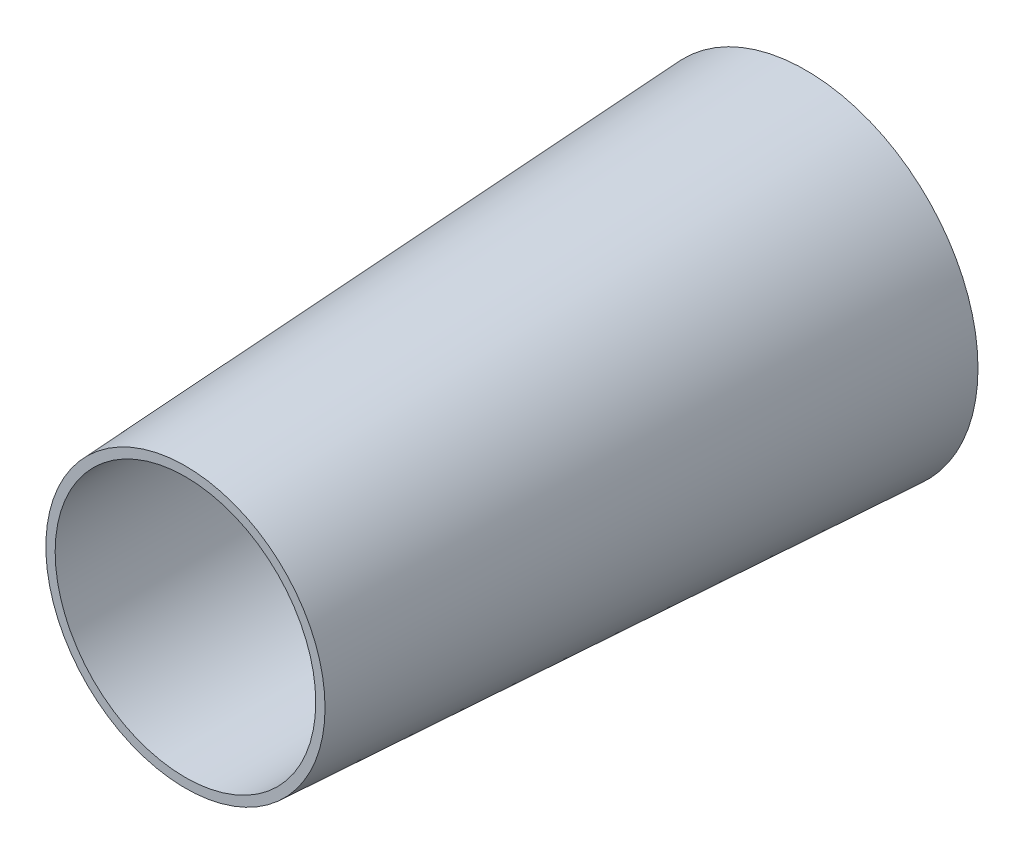
SolidWorks part; units mm, degrees
material "ABS"
ref_plane "Front Plane" through (0, 0, 0) normal (0, 0, 1) x (1, 0, 0)
ref_plane "Top Plane" through (0, 0, 0) normal (0, 1, 0) x (1, 0, 0)
ref_plane "Right Plane" through (0, 0, 0) normal (1, 0, 0) x (0, 0, -1)
sketch "Sketch1" plane through (0, 0, 0) normal (0, 0, 1) x (1, 0, 0)
  circle A0 centre (0, 0) radius 22.5
  dimension "D1" = 45
extrude "Boss-Extrude" add sketch "Sketch1" along normal blind 100
draft "Draft3" type of draft neutral plane draft angle 3 faces to draft 1 face at (22.5, 0, 100) neutral plane through (0, 0, 100) neutral plane normal (0, 0, 1) parameters "D1"=3
sketch "Sketch2" plane through (0, 0, 0) normal (0, 0, -1) x (-1, 0, 0)
  circle A0 centre (0, 0) radius 21
  dimension "D1" = 42
extrude "Cut-Extrude1" cut sketch "Sketch2" against normal through all
